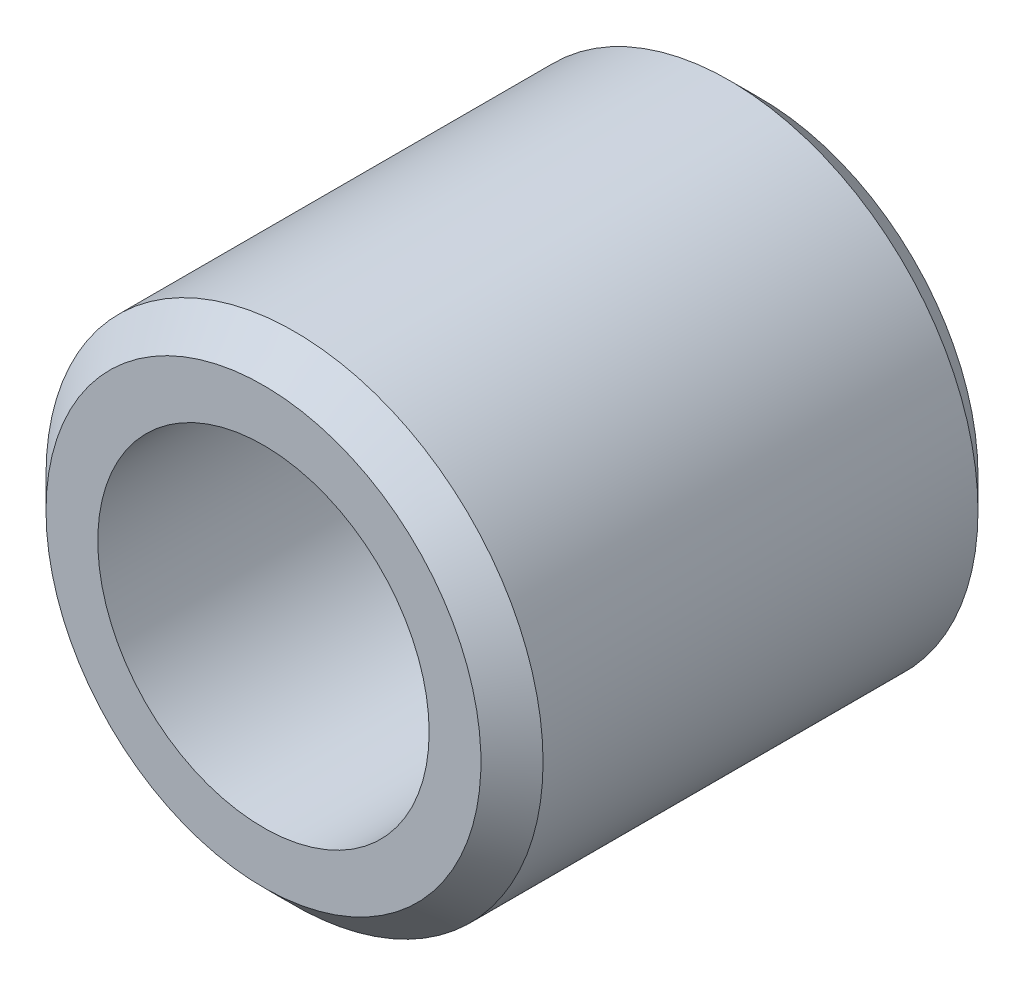
SolidWorks part; units mm, degrees
ref_plane "Front Plane" through (0, 0, 0) normal (0, 0, 1) x (1, 0, 0)
ref_plane "Top Plane" through (0, 0, 0) normal (0, 1, 0) x (1, 0, 0)
ref_plane "Right Plane" through (0, 0, 0) normal (1, 0, 0) x (0, 0, -1)
sketch "Sketch1" plane through (0, 0, 0) normal (1, 0, 0) x (0, 0, -1)
  line L0 (-4.7625, 0) -> (4.7625, 0) construction
  line L1 (4.7625, 4.7625) -> (4.7625, -4.7625) construction
  line L2 (-4.7625, 4.7625) -> (-4.7625, -4.7625) construction
  line L3 (4.7625, 4.7625) -> (-4.7625, 4.7625) construction
  line L4 (4.7625, -4.7625) -> (-4.7625, -4.7625) construction
  line L5 (-4.7625, 3.175) -> (4.7625, 3.175) construction
  line L6 (-4.7625, -3.175) -> (4.7625, -3.175) construction
  point P2 (0, 0)
  point P7 (-4.7625, 0)
  point P8 (-4.7625, -3.175)
  point P9 (4.7625, 0)
  point P11 (-4.7625, 3.175)
  dimension "OD" = 9.525
  dimension "ID" = 6.35
  dimension "Length" = 9.525
sketch "Sketch2" plane through (0, 0, 0) normal (0, 0, 1) x (1, 0, 0)
  line L0 (-4.7625, 0) -> (4.7625, 0) construction
  line L1 (0, -4.7625) -> (0, 4.7625) construction
  circle A0 centre (0, 0) radius 3.175 construction
  circle A1 centre (0, 0) radius 4.7625 construction
  point P16 (0, 0)
  dimension "ID" = 6.35
  dimension "OD" = 9.525
sketch "Sketch3" plane through (0, 0, 0) normal (1, 0, 0) x (0, 0, -1)
  line L0 (-4.7625, 3.175) -> (4.7625, 3.175)
  line L1 (4.7625, 4.7625) -> (4.7625, -4.7625) construction
  line L2 (4.7625, 3.175) -> (4.7625, 4.7625)
  line L5 (4.7625, 4.7625) -> (-4.7625, 4.7625)
  line L6 (-4.7625, 4.7625) -> (-4.7625, 3.175)
  line L7 (-4.7625, 0) -> (4.7625, 0) construction
revolve "Revolve1" add sketch "Sketch3" angle 360 about L7
chamfer "Chamfer1" distance 0.5953 angle 45 2 edges at (4.7625, 0, 4.7625) (4.7625, 0, -4.7625)
equation "\"D1@Chamfer1\"=((\"OD@Sketch1\"-\"ID@Sketch1\")/2)*.375"
